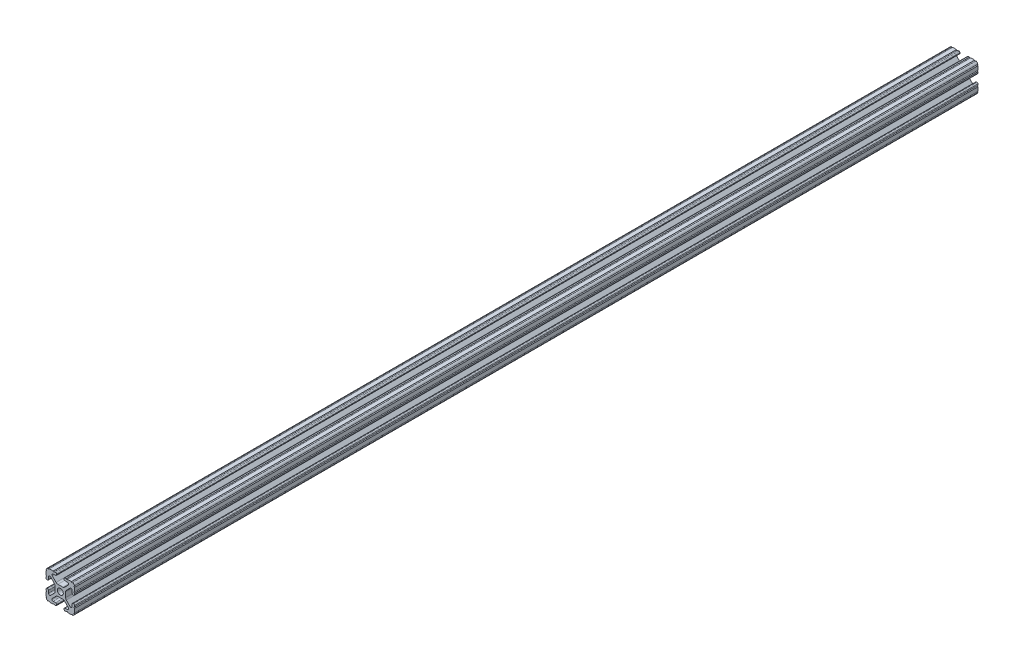
SolidWorks part; units mm, degrees
ref_plane "Front Plane" through (0, 0, 0) normal (0, 0, 1) x (1, 0, 0)
ref_plane "Top Plane" through (0, 0, 0) normal (0, 1, 0) x (1, 0, 0)
ref_plane "Right Plane" through (0, 0, 0) normal (1, 0, 0) x (0, 0, -1)
sketch "Sketch2" plane through (0, 0, 0) normal (0, 0, 1) x (1, 0, 0)
  line L0 (0, 12.7) -> (0, -12.7) construction
  line L1 (-12.7, 0) -> (12.7, 0) construction
  line L2 (3.2512, -12.7) -> (12.7, -12.7)
  line L3 (12.7, -12.7) -> (12.7, -3.2512)
  line L4 (3.2512, -12.7) -> (3.2512, -10.4902)
  line L5 (3.2512, -10.4902) -> (8.9276, -10.4902)
  line L6 (8.9276, -10.4902) -> (3.0856, -4.6482)
  line L7 (0, 0) -> (12.7, -12.7) construction
  line L8 (12.7, -3.2512) -> (10.4902, -3.2512)
  line L9 (10.4902, -3.2512) -> (10.4902, -8.9276)
  line L10 (10.4902, -8.9276) -> (4.6482, -3.0856)
  circle A0 centre (0, 0) radius 2.6035
  arc A1 (6.3485, -10.4902) -> (7.1039, -8.6665) centre (6.3485, -9.4219) ccw construction
  point P8 (0, -4.6482)
  dimension "Center Hole Diameter" = 5.207
  dimension "Rail Height" = 25.4
  dimension "Rail Width" = 25.4
  dimension "T-Slot Width" = 6.5024
  dimension "Slot Inner Width" = 14.8336
  dimension "Thickness" = 2.2098
  dimension "Slot Depth" = 5.842
  dimension "D1" = 2.2098
sketch "Sketch3" plane through (0, 0, 0) normal (1, 0, 0) x (0, 0, -1)
  line L0 (-400, -12.7) -> (400, -12.7) construction
  line L1 (-374.6, 0) -> (374.6, 0) construction
  dimension "Length" = 800
  dimension "D1" = 25.4
sketch "Sketch4" plane through (0, 0, 0) normal (0, 0, 1) x (1, 0, 0)
  line L0 (4.1904, -12.7) -> (10.1173, -12.7)
  line L1 (3.2512, -12.7) -> (12.7, -12.7) construction
  line L2 (3.2512, -12.7) -> (3.2512, -10.4902) construction
  line L3 (3.2512, -10.4902) -> (8.9276, -10.4902) construction
  line L4 (3.2512, -11.4294) -> (3.2512, -11.7608)
  line L5 (4.1904, -10.4902) -> (6.3485, -10.4902)
  line L6 (0, -4.6482) -> (2.164, -4.6482)
  line L7 (8.9276, -10.4902) -> (3.0856, -4.6482) construction
  line L8 (3.7373, -5.2999) -> (7.1039, -8.6665)
  line L9 (12.7, -12.7) -> (12.7, -3.2512) construction
  line L10 (10.4902, -8.9276) -> (4.6482, -3.0856) construction
  line L11 (10.4902, -3.2512) -> (10.4902, -8.9276) construction
  line L12 (10.4902, -6.3485) -> (10.4902, -4.1904)
  line L13 (12.7, -3.2512) -> (10.4902, -3.2512) construction
  line L14 (11.4294, -3.2512) -> (11.7608, -3.2512)
  line L15 (12.7, -4.1904) -> (12.7, -10.1173)
  line L16 (8.6665, -7.1039) -> (5.2999, -3.7373)
  line L17 (4.6482, 0) -> (4.6482, -2.164)
  line L18 (-12.7, 0) -> (12.7, 0) construction
  line L19 (0, -4.6482) -> (0, -2.6035)
  line L20 (0, 12.7) -> (0, -12.7) construction
  line L21 (4.6482, 0) -> (2.6035, 0)
  arc A0 (3.2512, -11.7608) -> (4.1904, -12.7) centre (4.1904, -11.7608) ccw
  arc A2 (3.2512, -11.4294) -> (4.1904, -10.4902) centre (4.1904, -11.4294) cw
  arc A3 (6.3485, -10.4902) -> (7.1039, -8.6665) centre (6.3485, -9.4219) ccw
  arc A4 (2.164, -4.6482) -> (3.7373, -5.2999) centre (2.164, -6.8732) cw
  arc A5 (10.1173, -12.7) -> (12.7, -10.1173) centre (10.1173, -10.1173) ccw
  arc A6 (8.6665, -7.1039) -> (10.4902, -6.3485) centre (9.4219, -6.3485) ccw
  arc A7 (10.4902, -4.1904) -> (11.4294, -3.2512) centre (11.4294, -4.1904) cw
  arc A8 (11.7608, -3.2512) -> (12.7, -4.1904) centre (11.7608, -4.1904) cw
  arc A9 (5.2999, -3.7373) -> (4.6482, -2.164) centre (6.8732, -2.164) cw
  circle A10 centre (0, 0) radius 2.6035 construction
  arc A11 (0, -2.6035) -> (2.6035, 0) centre (0, 0) ccw
  dimension "D1" = 2.5827
  dimension "D2" = 2.225
  dimension "D3" = 0.9392
extrude "Boss-Extrude1" add sketch "Sketch4" along normal mid plane 800
sketch "Sketch5" plane through (0, 0, 0) normal (0, 0, 1) x (1, 0, 0)
  line L0 (3.2512, -12.7) -> (12.7, -12.7) construction
  line L1 (4.1904, -10.4902) -> (6.3485, -10.4902) construction
  line L3 (0, 0) -> (12.7, -12.7) construction
  line L4 (6.3485, -10.4902) -> (6.3485, -12.7) construction
  line L5 (8.9276, -10.4902) -> (3.0856, -4.6482) construction
  circle A0 centre (10.3562, -12.7) radius 0.5524
  circle A1 centre (5.796, -12.7) radius 0.5524
  circle A2 centre (12.7, -10.3562) radius 0.5524
  circle A3 centre (12.7, -5.796) radius 0.5524
  point P10 (5.2694, -10.4902)
  point P12 (9.4219, -6.3485)
  dimension "D1" = 1.1049
extrude "Cut-Extrude1" cut sketch "Sketch5" against normal through all both and the other way through all
mirror "Mirror1" about plane through (0, 0, 0) normal (1, 0, 0) of bodies 137 134
mirror "Mirror2" about plane through (0, 0, 0) normal (0, 1, 0) of bodies 135
equation "\"D1@Boss-Extrude1\"=\"Length@Sketch3\""
equation "\"D1@Sketch2\"=\"Thickness@Sketch2\""
equation "\"D2@Sketch4\"=\"Slot Inner Width@Sketch2\"*0.15"
equation "\"D1@Sketch4\"=\"D3@Sketch4\"*2.75"
equation "\"D3@Sketch4\"=\"Thickness@Sketch2\"*0.425"
equation "\"D1@Sketch5\"=\"Thickness@Sketch2\"*0.5"
